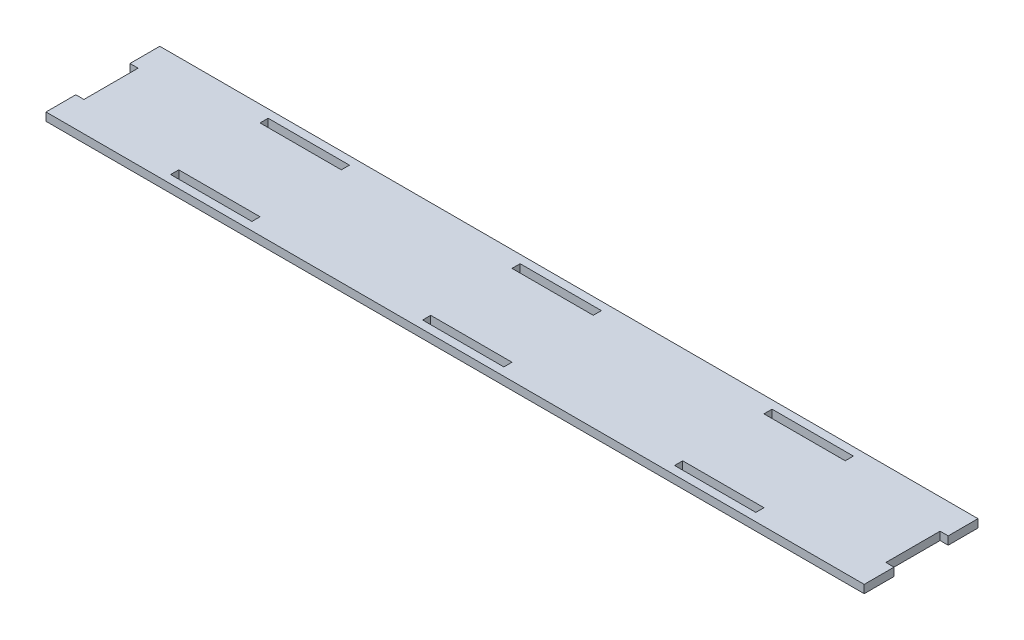
SolidWorks part; units mm, degrees
material "ABS"
ref_plane "Front Plane" through (0, 0, 0) normal (0, 0, 1) x (1, 0, 0)
ref_plane "Top Plane" through (0, 0, 0) normal (0, 1, 0) x (1, 0, 0)
ref_plane "Right Plane" through (0, 0, 0) normal (1, 0, 0) x (0, 0, -1)
sketch "Sketch1" plane through (0, 0, 0) normal (0, 1, 0) x (1, 0, 0)
  line L0 (0, 31) -> (0, 42)
  line L1 (0, 0) -> (302, 0)
  line L2 (0, 0) -> (0, 11)
  line L3 (0, 42) -> (302, 42)
  line L4 (302, 0) -> (302, 11)
  line L5 (302, 31) -> (299, 31)
  line L7 (302, 11) -> (299, 11)
  line L8 (299, 31) -> (299, 11)
  line L9 (0, 31) -> (3, 31)
  line L11 (0, 11) -> (3, 11)
  line L12 (3, 31) -> (3, 11)
  line L13 (302, 31) -> (302, 42)
  line L14 (299, 21) -> (128.5685, 21) construction
  line L15 (259, 3) -> (259, 6.0028)
  line L16 (43, 38.9972) -> (73, 38.9972)
  line L17 (43, 38.9972) -> (43, 35.9972)
  line L18 (43, 35.9972) -> (73, 35.9972)
  line L19 (73, 38.9972) -> (73, 35.9972)
  line L20 (136, 39) -> (166, 39)
  line L21 (136, 39) -> (136, 36)
  line L22 (136, 36) -> (166, 36)
  line L23 (166, 39) -> (166, 36)
  line L24 (229, 39) -> (259, 39)
  line L25 (229, 39) -> (229, 35.9972)
  line L26 (229, 35.9972) -> (259, 35.9972)
  line L27 (259, 39) -> (259, 35.9972)
  line L28 (229, 6.0028) -> (259, 6.0028)
  line L29 (229, 3) -> (229, 6.0028)
  line L30 (229, 3) -> (259, 3)
  line L31 (166, 3) -> (166, 6)
  line L32 (136, 6) -> (166, 6)
  line L33 (136, 3) -> (136, 6)
  line L34 (136, 3) -> (166, 3)
  line L35 (73, 3.0028) -> (73, 6.0028)
  line L36 (43, 6.0028) -> (73, 6.0028)
  line L37 (43, 3.0028) -> (43, 6.0028)
  line L38 (43, 3.0028) -> (73, 3.0028)
  point P27 (244, 39)
  dimension "D1" = 302
  dimension "D2" = 42
  dimension "D3" = 3
  dimension "D4" = 20
  dimension "D5" = 11
  dimension "D6" = 20
  dimension "D7" = 3
  dimension "D8" = 11
  dimension "D9" = 30
  dimension "D10" = 30
  dimension "D11" = 30
  dimension "D12" = 3
  dimension "D13" = 3.0028
  dimension "D14" = 3
  dimension "D15" = 3
  dimension "D16" = 3
  dimension "D17" = 3.0028
  dimension "D18" = 43
  dimension "D19" = 43
  dimension "D20" = 63
extrude "Boss-Extrude1" add sketch "Sketch1" along normal blind 3
